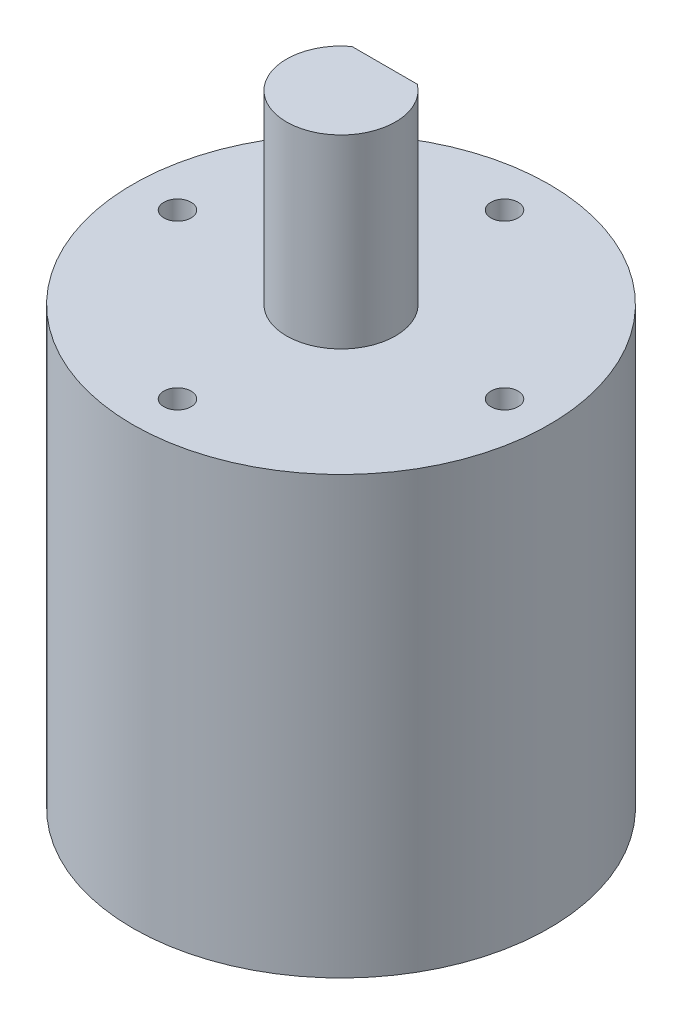
SolidWorks part; units mm, degrees
ref_plane "前视基准面" through (0, 0, 0) normal (0, 0, 1) x (1, 0, 0)
ref_plane "上视基准面" through (0, 0, 0) normal (0, 1, 0) x (1, 0, 0)
ref_plane "右视基准面" through (0, 0, 0) normal (1, 0, 0) x (0, 0, -1)
sketch "草图1" plane through (0, 0, 0) normal (0, 1, 0) x (1, 0, 0)
  circle A0 centre (0, 0) radius 19.1
  dimension "D1" = 38.2
extrude "凸台-拉伸1" add sketch "草图1" along normal blind 40
sketch "草图2" plane through (0, 40, 0) normal (0, 1, 0) x (1, 0, 0)
  circle A0 centre (0, 0) radius 5
  dimension "D1" = 10
extrude "凸台-拉伸2" add sketch "草图2" along normal blind 17
sketch "草图3" plane through (0, 57, 0) normal (0, 1, 0) x (1, 0, 0)
  line L0 (0, 5) -> (0, 0) construction
  line L1 (-3, 4) -> (3, 4)
  arc A0 (3, 4) -> (-3, 4) centre (0, 0) ccw
  dimension "D2" = 10
  dimension "D1" = 4
extrude "切除-拉伸1" cut sketch "草图3" against normal blind 15
sketch "草图4" plane through (0, 40, 0) normal (0, 1, 0) x (1, 0, 0)
  circle A0 centre (0, 0) radius 15 construction
  circle A1 centre (0, 15) radius 1.5 construction
  circle A2 centre (15, 0) radius 1.5 construction
  circle A3 centre (0, -15) radius 1.5 construction
  circle A4 centre (-15, 0) radius 1.5 construction
  point P14 (0, 0)
  dimension "D1" = 30
  dimension "D2" = 3
  dimension "D3" = 4
hole_wizard "M3 螺纹孔1" positions "3D草图1" profile "草图5" tap size "M3" standard "GB"
sketch3d "3D草图1"
  point P0 (0, 40, -15)
  point P3 (-15, 40, 0)
  point P6 (15, 40, 0)
  point P9 (0, 40, 15)
sketch "草图5" plane through (0, 40, -15) normal (1, 0, 0) x (0, 0, 1)
  line L0 (0, 0) -> (0, 9.2217)
  line L1 (0, 9.2217) -> (1.25, 8.5)
  line L2 (1.25, 8.5) -> (1.25, 0)
  line L5 (1.25, 0) -> (0, 0)
  line L10 (0, 9.2217) -> (-1.25, 8.5) construction
  line L11 (0, -6.35) -> (0, 107.95) construction
  dimension "螺纹孔钻头直径" = 2.5
  dimension "螺纹孔钻头深度" = 8.5
  dimension "导头角度" = 120
cosmetic thread "孔螺蚊线1" parameters "D1"=6, "D2"=3
cosmetic thread "孔螺蚊线2" parameters "D1"=6, "D2"=3
cosmetic thread "孔螺蚊线3" parameters "D1"=6, "D2"=3
cosmetic thread "孔螺蚊线4" parameters "D1"=6, "D2"=3
